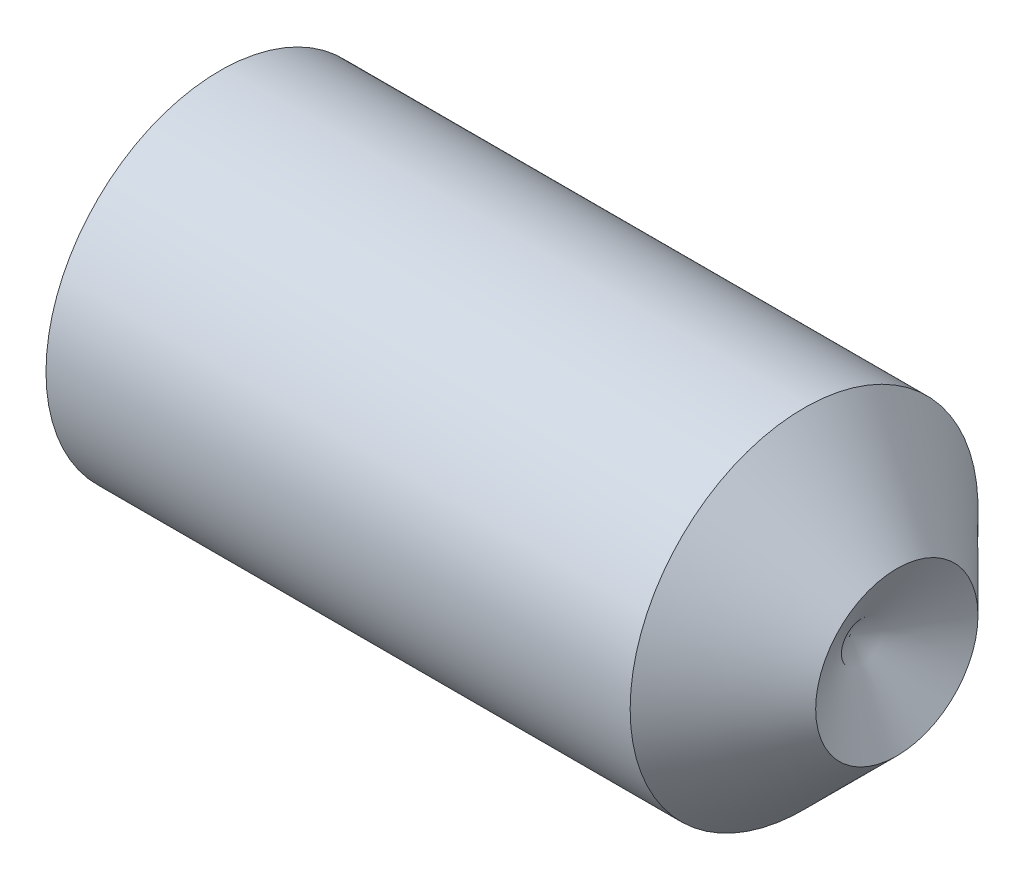
SolidWorks part; units mm, degrees
revolve "BaseBody" add sketch "BodySke" angle 360 about L5
sketch "BodySke" plane through (0, 0, 0) normal (0, 0, 1) x (1, 0, 0)
  line L0 (0, 0) -> (0, 1.2195)
  line L1 (0, 1.2195) -> (0.1619, 1.5)
  line L2 (0.1619, 1.5) -> (5.2, 1.5)
  line L3 (5.2, 1.5) -> (6, 0.7)
  line L4 (5.5959, 0) -> (0, 0)
  line L5 (-12.7, 0) -> (88.9, 0) construction
  line L6 (5.5959, 0) -> (6, 0.7)
  line L7 (6, 0.7) -> (6, 10.225) construction
  line L8 (0, -1.2195) -> (0.1619, -1.5) construction
  line L9 (5.5959, 0) -> (6, -0.7) construction
  line L10 (5.2, -1.5) -> (6, -0.7) construction
  line L11 (0.25, 15.875) -> (0.25, -3.175) construction
  dimension "Diameter" = 3
  dimension "Drive_ch_ang" = 60
  dimension "Minor_dia" = 2.439
  dimension "Cup_ang" = 120
  dimension "Cup_dia" = 1.4
  dimension "Length" = 6
  dimension "Cup_nose_ang" = 45
  dimension "Advance" = 0.5
cosmetic thread "ThreadCosmetic" [suppressed] parameters "Thread_minor"=2.439
ref_plane "Plane1" through (0, 0, 0) normal (0, 0, 1) x (1, 0, 0)
ref_plane "Plane2" through (0, 0, 0) normal (0, 1, 0) x (1, 0, 0)
ref_plane "Plane3" through (0, 0, 0) normal (1, 0, 0) x (0, 0, -1)
other "Configuration Table"
sketch "Sketch2" plane through (0, 0, 0) normal (-1, 0, 0) x (0, 0, 1)
  line L0 (0.433, 0.75) -> (-0.433, 0.75)
  line L1 (-0.433, 0.75) -> (-0.866, 0)
  line L2 (0.433, 0.75) -> (0.866, 0)
  line L3 (0.433, -0.75) -> (0.866, 0)
  line L4 (0.433, -0.75) -> (-0.433, -0.75)
  line L5 (-0.433, -0.75) -> (-0.866, 0)
  dimension "Hex_size" = 1.5
  dimension "D2" = 0.75
  dimension "D3" = 0.75
extrude "Hex" cut sketch "Sketch2" against normal blind 2
sketch "ThdSchSke" plane through (0, 0, 0) normal (0, 0, 1) x (1, 0, 0)
  line L0 (0.1619, -1.2195) -> (-0.0345, -1.5)
  line L1 (0.1619, -1.2195) -> (0.3584, -1.5)
  line L2 (0.3584, -1.5) -> (0.3584, -1.875)
  line L3 (-3.175, 0) -> (5.1513, 0) construction
  line L4 (0.1619, 1.5) -> (0.1619, -1.5) construction
  line L5 (0.3584, -1.875) -> (-0.0345, -1.875)
  line L6 (-0.0345, -1.875) -> (-0.0345, -1.5)
  dimension "Thread_minor" = 2.439
  dimension "Diameter" = 3
revolve "ThreadSchematic" [suppressed] cut sketch "ThdSchSke" angle 360 about L3
pattern_linear "ThdSchPat" [suppressed]
equation "\"D2@Sketch2\" = \"Hex_size@Sketch2\" / 2"
equation "\"D3@Sketch2\" = \"Hex_size@Sketch2\" / 2"
equation "\"Thread_minor@ThreadCosmetic\" = \"Minor_dia@BodySke\""
equation "\"Thread_minor@ThdSchSke\" = \"Thread_minor@ThreadCosmetic\""
equation "\"Diameter@ThdSchSke\" = \"Diameter@BodySke\""
equation "\"Overcut@ThdSchSke\" = \"Diameter@BodySke\" * 1.25"
equation "\"Num_threads@ThdSchPat\" = int( (\"Length@BodySke\" - ( ( ( \"Diameter@BodySke\" - \"Minor_dia@BodySke\" ) * 0.5 ) / tan( \"Drive_ch_ang@BodySke\" * 0.017453292 ) ) - ( ( ( \"Diameter@BodySke\" - \"Cup_dia@BodySke\" ) * 0.5 ) * tan( \"Cup_nose_ang@BodySke\" * 0.017453292 ) ) ) / \"Advance@BodySke\" + 0.999 )  + 1"
equation "\"Advance@ThdSchPat\" = (\"Length@BodySke\" - ( ( ( \"Diameter@BodySke\" - \"Minor_dia@BodySke\" ) * 0.5 ) / tan( \"Drive_ch_ang@BodySke\" * 0.017453292 ) ) - ( ( ( \"Diameter@BodySke\" - \"Cup_dia@BodySke\" ) * 0.5 ) * tan( \"Cup_nose_ang@BodySke\" * 0.017453292 ) ) ) /  (\"Num_threads@ThdSchPat\" - 1) 'relax it"
equation "' \"Num_threads@ThdSchPat\" = \"Num_threads@ThdSchPat\" - sgn( \"Num_threads@ThdSchPat\" - 1) '---chamfered tips only---"
